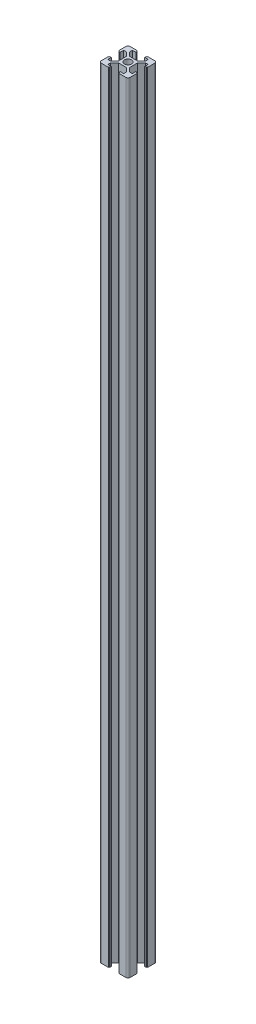
SolidWorks part; units mm, degrees
ref_plane "前视基准面" through (0, 0, 0) normal (0, 0, 1) x (1, 0, 0)
ref_plane "上视基准面" through (0, 0, 0) normal (0, 1, 0) x (1, 0, 0)
ref_plane "右视基准面" through (0, 0, 0) normal (1, 0, 0) x (0, 0, -1)
other "Configuration Table"
sketch "草图2" plane through (0, 0, 0) normal (0, 1, 0) x (1, 0, 0)
  line L0 (-3.6, 10) -> (-3.6, 9.5)
  line L1 (-3.6, 9.5) -> (-3.1, 9.5)
  line L2 (-3.1, 9.5) -> (-3.1, 8.5)
  line L3 (-3.1, 8.5) -> (-5.5, 8.5)
  line L4 (-8.5, -10) -> (-3.6, -10)
  line L5 (-10, -8.5) -> (-10, -3.6)
  line L6 (8.5, 10) -> (3.6, 10)
  line L7 (10, 8.5) -> (10, 3.6)
  line L8 (0, 14.8756) -> (0, 0) construction
  line L9 (0, 0) -> (14.1675, 0) construction
  line L10 (-5.5, 8.5) -> (-5.5, 6.65)
  line L11 (-5.5, 6.65) -> (-2.75, 3.9)
  line L12 (-2.75, 3.9) -> (2.75, 3.9)
  line L13 (5.5, 6.65) -> (2.75, 3.9)
  line L14 (5.5, 8.5) -> (5.5, 6.65)
  line L15 (3.1, 8.5) -> (5.5, 8.5)
  line L16 (3.1, 9.5) -> (3.1, 8.5)
  line L17 (3.6, 9.5) -> (3.1, 9.5)
  line L18 (3.6, 10) -> (3.6, 9.5)
  line L19 (-3.6, 10) -> (-8.5, 10)
  line L20 (10, 3.6) -> (9.5, 3.6)
  line L21 (9.5, 3.6) -> (9.5, 3.1)
  line L22 (9.5, 3.1) -> (8.5, 3.1)
  line L23 (8.5, 3.1) -> (8.5, 5.5)
  line L24 (8.5, 5.5) -> (6.65, 5.5)
  line L25 (6.65, 5.5) -> (3.9, 2.75)
  line L26 (3.9, 2.75) -> (3.9, -2.75)
  line L27 (6.65, -5.5) -> (3.9, -2.75)
  line L28 (8.5, -5.5) -> (6.65, -5.5)
  line L29 (8.5, -3.1) -> (8.5, -5.5)
  line L30 (9.5, -3.1) -> (8.5, -3.1)
  line L31 (9.5, -3.6) -> (9.5, -3.1)
  line L32 (10, -3.6) -> (9.5, -3.6)
  line L33 (3.6, -10) -> (3.6, -9.5)
  line L34 (3.6, -9.5) -> (3.1, -9.5)
  line L35 (3.1, -9.5) -> (3.1, -8.5)
  line L36 (3.1, -8.5) -> (5.5, -8.5)
  line L37 (5.5, -8.5) -> (5.5, -6.65)
  line L38 (5.5, -6.65) -> (2.75, -3.9)
  line L39 (2.75, -3.9) -> (-2.75, -3.9)
  line L40 (-5.5, -6.65) -> (-2.75, -3.9)
  line L41 (-5.5, -8.5) -> (-5.5, -6.65)
  line L42 (-3.1, -8.5) -> (-5.5, -8.5)
  line L43 (-3.1, -9.5) -> (-3.1, -8.5)
  line L44 (-3.6, -9.5) -> (-3.1, -9.5)
  line L45 (-3.6, -10) -> (-3.6, -9.5)
  line L46 (-10, -3.6) -> (-9.5, -3.6)
  line L47 (-9.5, -3.6) -> (-9.5, -3.1)
  line L48 (-9.5, -3.1) -> (-8.5, -3.1)
  line L49 (-8.5, -3.1) -> (-8.5, -5.5)
  line L50 (-8.5, -5.5) -> (-6.65, -5.5)
  line L51 (-6.65, -5.5) -> (-3.9, -2.75)
  line L52 (-3.9, -2.75) -> (-3.9, 2.75)
  line L53 (-6.65, 5.5) -> (-3.9, 2.75)
  line L54 (-8.5, 5.5) -> (-6.65, 5.5)
  line L55 (-8.5, 3.1) -> (-8.5, 5.5)
  line L56 (-9.5, 3.1) -> (-8.5, 3.1)
  line L57 (-9.5, 3.6) -> (-9.5, 3.1)
  line L58 (-10, 3.6) -> (-9.5, 3.6)
  line L59 (3.6, -10) -> (8.5, -10)
  line L60 (-10, 3.6) -> (-10, 8.5)
  line L61 (10, -3.6) -> (10, -8.5)
  circle A0 centre (0, 0) radius 2.5
  arc A1 (-10, 8.5) -> (-8.5, 10) centre (-8.5, 8.5) cw
  arc A2 (10, 8.5) -> (8.5, 10) centre (8.5, 8.5) ccw
  arc A3 (-8.5, -10) -> (-10, -8.5) centre (-8.5, -8.5) cw
  arc A4 (8.5, -10) -> (10, -8.5) centre (8.5, -8.5) ccw
  point P0 (-10, 0)
  point P1 (10, 0)
  point P2 (0, 10)
  point P3 (0, -10)
  point P4 (0, 0)
  point P5 (-10, -10)
  point P6 (10, -10)
  point P7 (10, 10)
  point P8 (-10, 10)
  point P36 (-10, 10)
  point P39 (10, 10)
  dimension "D1" = 11
  dimension "D2" = 20
  dimension "D3" = 6.2
  dimension "D4" = 7.2
  dimension "D5" = 6.1
  dimension "D6" = 5
  dimension "D7" = 1.5
  dimension "D8" = 45
  dimension "D9" = 0.5
  dimension "D10" = 1
  dimension "D11" = 5.5
extrude "凸台-拉伸1" add sketch "草图2" along normal blind 540
